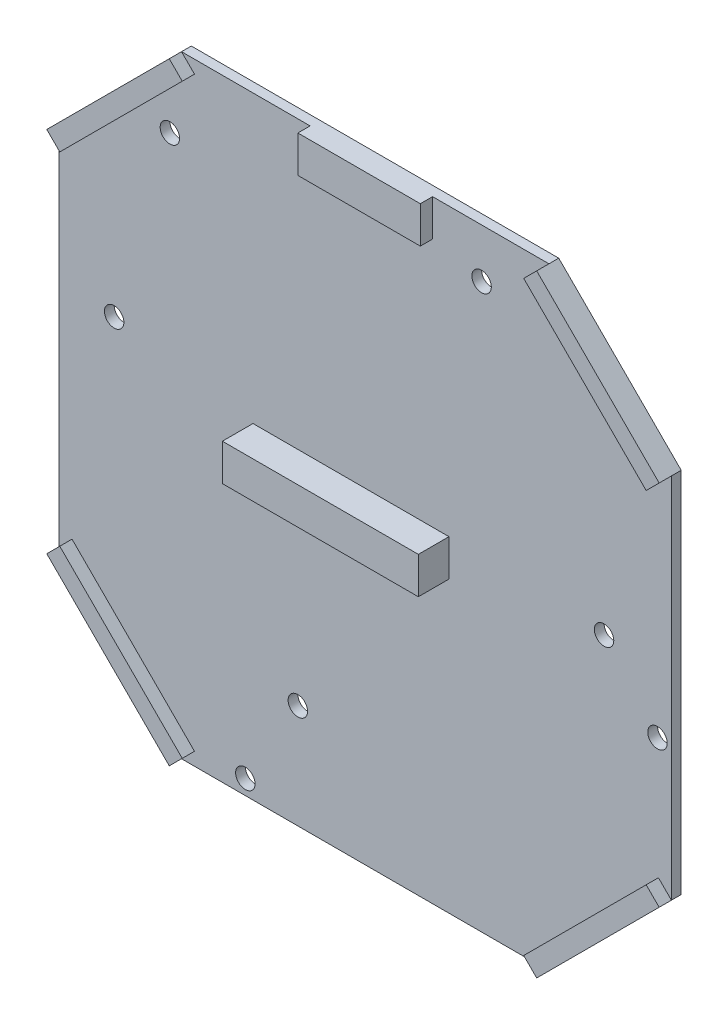
SolidWorks part; units mm, degrees
ref_plane "Front Plane" through (0, 0, 0) normal (0, 0, 1) x (1, 0, 0)
ref_plane "Top Plane" through (0, 0, 0) normal (0, 1, 0) x (1, 0, 0)
ref_plane "Right Plane" through (0, 0, 0) normal (1, 0, 0) x (0, 0, -1)
sketch "Sketch1" plane through (0, 0, 0) normal (0, 0, 1) x (1, 0, 0)
  line L1 (-34.7243, 77.3309) -> (65.2757, 77.3309)
  line L2 (-34.7243, 77.3309) -> (-34.7243, -22.6691)
  line L3 (-34.7243, -22.6691) -> (65.2757, -22.6691)
  line L4 (65.2757, 77.3309) -> (65.2757, -22.6691)
  dimension "D1" = 100
  dimension "D2" = 100
extrude "Boss-Extrude1" add sketch "Sketch1" along normal blind 1.6
sketch "Sketch2" plane through (0, 0, 1.6) normal (0, 0, 1) x (1, 0, 0)
  line L0 (-34.7243, 57.3309) -> (-14.7243, 77.3309)
  line L1 (-34.7243, 77.3309) -> (-34.7243, -22.6691) construction
  line L2 (65.2757, 77.3309) -> (-34.7243, 77.3309) construction
  line L3 (-14.7243, 77.3309) -> (-34.7243, 77.3309)
  line L4 (-34.7243, 77.3309) -> (-34.7243, 57.3309)
  line L5 (-34.7243, -2.6691) -> (-14.7243, -22.6691)
  line L6 (-34.7243, -22.6691) -> (65.2757, -22.6691) construction
  line L7 (-14.7243, -22.6691) -> (-34.7243, -22.6691)
  line L8 (-34.7243, -22.6691) -> (-34.7243, -2.6691)
  line L9 (45.2757, 77.3309) -> (65.2757, 57.3309)
  line L10 (65.2757, -22.6691) -> (65.2757, 77.3309) construction
  line L11 (65.2757, 57.3309) -> (65.2757, 77.3309)
  line L12 (65.2757, 77.3309) -> (45.2757, 77.3309)
  line L13 (65.2757, -2.6691) -> (45.2757, -22.6691)
  line L14 (45.2757, -22.6691) -> (65.2757, -22.6691)
  line L15 (65.2757, -22.6691) -> (65.2757, -2.6691)
  dimension "D1" = 20
  dimension "D2" = 20
  dimension "D3" = 20
  dimension "D4" = 20
  dimension "D5" = 20
  dimension "D6" = 20
  dimension "D7" = 20
  dimension "D8" = 20
extrude "Cut-Extrude1" cut sketch "Sketch2" against normal blind 1.6
sketch "Sketch7" plane through (0, 0, 1.6) normal (0, 0, 1) x (1, 0, 0)
  line L0 (45.2757, 77.3309) -> (-14.7243, 77.3309) construction
  line L1 (-34.7243, 57.3309) -> (-34.7243, -2.6691) construction
  line L2 (65.2757, -2.6691) -> (65.2757, 57.3309) construction
  line L3 (-14.7243, -22.6691) -> (45.2757, -22.6691) construction
  circle A0 centre (-25.7243, 34.3309) radius 1.5875
  circle A1 centre (-16.6243, 64.9049) radius 1.5875
  circle A2 centre (34.2757, 69.3309) radius 1.5875
  circle A3 centre (54.2757, 29.3309) radius 1.5875
  circle A4 centre (62.9997, 19.1809) radius 1.5875
  circle A5 centre (-4.3003, -20.2191) radius 1.5875
  circle A6 centre (4.2757, -5.6691) radius 1.5875
  dimension "D1" = 3.175
  dimension "D16" = 3.175
  dimension "D17" = 3.175
  dimension "D18" = 3.175
  dimension "D19" = 3.175
  dimension "D20" = 3.175
  dimension "D21" = 3.175
  dimension "D2" = 43
  dimension "D3" = 9
  dimension "D4" = 12.426
  dimension "D5" = 18.1
  dimension "D6" = 8
  dimension "D7" = 31
  dimension "D8" = 11
  dimension "D9" = 48
  dimension "D10" = 58.15
  dimension "D11" = 97.724
  dimension "D12" = 39
  dimension "D13" = 17
  dimension "D14" = 30.424
  dimension "D15" = 97.55
extrude "Cut-Extrude2" cut sketch "Sketch7" against normal blind 1.6
sketch "Sketch8" plane through (0, 0, 1.6) normal (0, 0, 1) x (1, 0, 0)
  line L0 (45.2757, 77.3309) -> (-14.7243, 77.3309) construction
  line L1 (-3.0503, 30.5809) -> (28.9497, 30.5809)
  line L2 (-3.0503, 30.5809) -> (-3.0503, 24.5809)
  line L3 (-3.0503, 24.5809) -> (28.9497, 24.5809)
  line L4 (28.9497, 30.5809) -> (28.9497, 24.5809)
  line L5 (-34.7243, 57.3309) -> (-34.7243, -2.6691) construction
  dimension "D1" = 46.75
  dimension "D2" = 31.674
  dimension "D3" = 32
  dimension "D4" = 6
extrude "Boss-Extrude2" add sketch "Sketch8" along normal blind 5
sketch "Sketch10" plane through (0, 0, 1.6) normal (0, 0, 1) x (1, 0, 0)
  line L0 (-34.7243, 57.3309) -> (-14.7243, 77.3309)
  line L1 (-34.7243, 57.3309) -> (-32.603, 55.2096)
  line L2 (-14.7243, 77.3309) -> (-12.603, 75.2096)
  line L3 (-32.603, 55.2096) -> (-12.603, 75.2096)
  line L4 (-34.7243, 57.3309) -> (-14.7243, 77.3309) construction
  line L5 (45.2757, 77.3309) -> (65.2757, 57.3309)
  line L6 (45.2757, 77.3309) -> (43.1543, 75.2096)
  line L7 (65.2757, 57.3309) -> (63.1543, 55.2096)
  line L8 (43.1543, 75.2096) -> (63.1543, 55.2096)
  line L9 (45.2757, 77.3309) -> (65.2757, 57.3309) construction
  line L10 (65.2757, -2.6691) -> (45.2757, -22.6691)
  line L11 (65.2757, -2.6691) -> (63.1543, -0.5478)
  line L12 (45.2757, -22.6691) -> (43.1543, -20.5478)
  line L13 (63.1543, -0.5478) -> (43.1543, -20.5478)
  line L14 (65.2757, -2.6691) -> (45.2757, -22.6691) construction
  line L15 (-14.7243, -22.6691) -> (-34.7243, -2.6691)
  line L16 (-14.7243, -22.6691) -> (-12.603, -20.5478)
  line L17 (-34.7243, -2.6691) -> (-32.603, -0.5478)
  line L18 (-12.603, -20.5478) -> (-32.603, -0.5478)
  line L19 (-14.7243, -22.6691) -> (-34.7243, -2.6691) construction
  dimension "D1" = 3
  dimension "D2" = 3
  dimension "D3" = 3
  dimension "D4" = 3
extrude "Boss-Extrude3" add sketch "Sketch10" along normal blind 2
sketch "Sketch12" plane through (0, 0, 1.6) normal (0, 0, 1) x (1, 0, 0)
  line L0 (-34.7243, 57.3309) -> (-34.7243, -2.6691) construction
  line L1 (6.2757, 77.3309) -> (26.2757, 77.3309)
  line L2 (6.2757, 77.3309) -> (6.2757, 71.3309)
  line L3 (6.2757, 71.3309) -> (26.2757, 71.3309)
  line L4 (26.2757, 77.3309) -> (26.2757, 71.3309)
  line L5 (45.2757, 77.3309) -> (-14.7243, 77.3309) construction
  dimension "D1" = 20
  dimension "D2" = 6
  dimension "D3" = 41
extrude "Boss-Extrude5" add sketch "Sketch12" along normal blind 2
